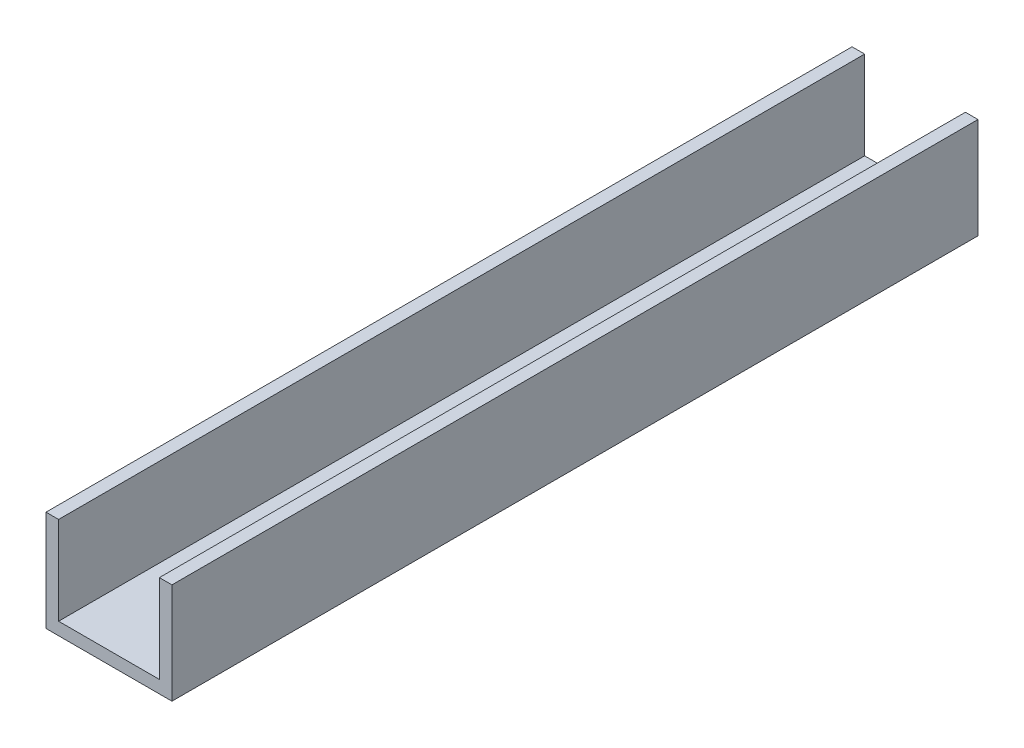
SolidWorks part; units mm, degrees
ref_plane "Front" through (0, 0, 0) normal (0, 0, 1) x (1, 0, 0)
ref_plane "Top" through (0, 0, 0) normal (0, 1, 0) x (1, 0, 0)
ref_plane "Right" through (0, 0, 0) normal (1, 0, 0) x (0, 0, -1)
sketch "Sketch1" plane through (0, 0, 0) normal (0, 0, 1) x (1, 0, 0)
  line L0 (0, -12.7) -> (0, 12.7) construction
  line L1 (-15.875, 0) -> (15.875, 0) construction
  line L2 (12.7, 12.7) -> (-12.7, 12.7) construction
  line L3 (-15.875, -12.7) -> (15.875, -12.7)
  line L4 (-15.875, -12.7) -> (-15.875, 12.7)
  line L5 (-15.875, 12.7) -> (15.875, 12.7)
  line L6 (15.875, -12.7) -> (15.875, 12.7)
  line L7 (-15.875, -12.7) -> (15.875, 12.7) construction
  line L8 (-15.875, 12.7) -> (15.875, -12.7) construction
  line L9 (-12.7, -12.7) -> (12.7, -12.7)
  point P3 (0, 0)
  point P4 (0, 0)
  point P8 (0, 0)
  point P13 (15.875, -9.525)
  point P17 (0, 12.7)
  point P20 (0, -12.7)
  dimension "Outside Width" = 31.75
  dimension "Outside Height" = 25.4
  dimension "Inside Height" = 22.225
  dimension "Wall Thickness" = 3.175
  dimension "Inside Width" = 25.4
sketch "Sketch2" plane through (0, 0, 0) normal (1, 0, 0) x (0, 0, -1)
  line L0 (-609.6, 0) -> (609.6, 0) construction
  dimension "Length" = 1219.2
sketch "Sketch3" plane through (0, 0, 0) normal (0, 0, 1) x (1, 0, 0)
  line L0 (-15.875, 12.7) -> (-15.875, -12.7)
  line L1 (-15.875, -12.7) -> (15.875, -12.7)
  line L2 (15.875, -12.7) -> (15.875, 12.7)
  line L3 (15.875, 12.7) -> (12.7, 12.7)
  line L4 (12.7, 12.7) -> (12.7, -9.525)
  line L5 (12.7, -9.525) -> (-12.7, -9.525)
  line L6 (-12.7, -9.525) -> (-12.7, 12.7)
  line L7 (-12.7, 12.7) -> (-15.875, 12.7)
  line L8 (-12.7, -9.525) -> (-12.7, -12.7) construction
  dimension "D1" = 25.4
  dimension "D2" = 31.75
  dimension "D3" = 3.175
extrude "Boss-Extrude2" add sketch "Sketch3" along normal mid plane 1219.2
sketch "Reference Sketch1" plane through (0, 0, 0) normal (1, 0, 0) x (0, 0, -1)
  line L0 (-609.6, 0) -> (609.6, 0) construction
  point P0 (-565.15, 0)
  point P1 (565.15, 0)
  dimension "D1" = 44.45
  dimension "D2" = 44.45
ref_plane "Plane1" through (12.7, -9.525, 609.6) normal (0, -1, 0) x (-1, 0, 0)
sketch "Sketch5" plane through (0, 0, 609.6) normal (0, 0, 1) x (1, 0, 0)
  line L0 (-15.875, 12.7) -> (-12.7, 12.7)
  line L1 (-12.7, 12.7) -> (-12.7, -9.525)
  line L2 (-12.7, -9.525) -> (12.7, -9.525)
  line L3 (12.7, -9.525) -> (12.7, 12.7)
  line L4 (12.7, 12.7) -> (15.875, 12.7)
  line L5 (15.875, 12.7) -> (15.875, -12.7)
  line L6 (15.875, -12.7) -> (-15.875, -12.7)
  line L7 (-15.875, -12.7) -> (-15.875, 12.7)
extrude "Cut-Extrude1" cut sketch "Sketch5" against normal blind 1016
sketch "Sketch6" plane through (0, -9.525, 0) normal (0, 1, 0) x (1, 0, 0)
  line L0 (12.7, 609.6) -> (-12.7, 609.6) construction
  line L1 (12.7, 406.4) -> (12.7, 609.6) construction
  point P0 (0, 594.6)
  dimension "D1" = 15
  dimension "D2" = 12.7
hole_wizard "M6 Clearance Hole1" positions "Sketch6" profile "Sketch7" hole size "M6" standard "ANSI Metric" end condition through all
sketch "Sketch7" plane through (0, -9.525, -594.6) normal (1, 0, 0) x (0, 0, 1)
  line L0 (0, 0) -> (0, 3.175)
  line L1 (0, 3.175) -> (3.2, 3.175)
  line L2 (3.2, 3.175) -> (3.2, 0)
  line L5 (3.2, 0) -> (0, 0)
  line L11 (0, -6.35) -> (0, 107.95) construction
  dimension "Thru Hole Dia." = 6.4
  dimension "Thru Hole Depth" = 3.175
equation "\"D1@Sketch3\" = \"Outside Height@Sketch1\""
equation "\"D2@Sketch3\" = \"Outside Width@Sketch1\""
equation "\"D3@Sketch3\" = \"Wall Thickness@Sketch1\""
equation "\"D1@Reference Sketch1\"=\"Outside Height@Sketch1\" * 1.75"
equation "\"D2@Reference Sketch1\" = \"D1@Reference Sketch1\""
equation "\"D1@Boss-Extrude2\" = \"Length@Sketch2\""
equation "\"Inside Height@Sketch1\"=\"Outside Height@Sketch1\"-\"Wall Thickness@Sketch1\""
equation "\"Inside Width@Sketch1\"=\"Outside Width@Sketch1\"-\"Wall Thickness@Sketch1\"*2"
